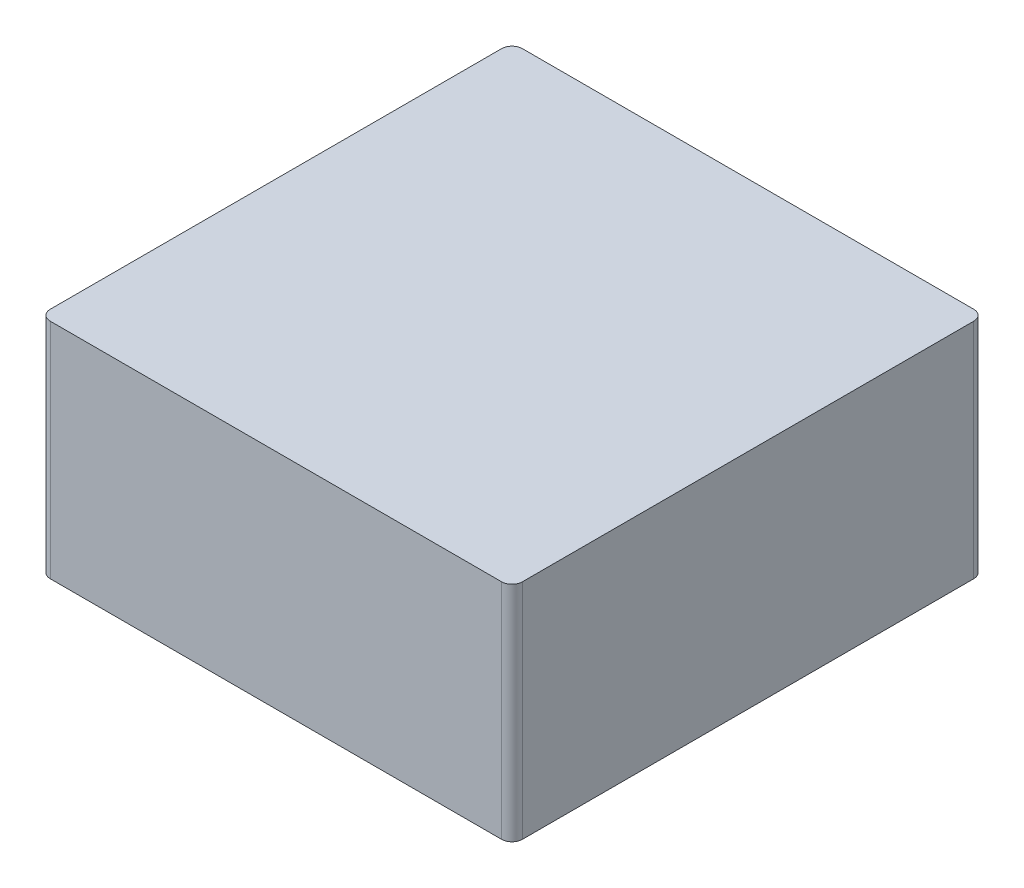
SolidWorks part; units mm, degrees
ref_plane "Front Plane" through (0, 0, 0) normal (0, 0, 1) x (1, 0, 0)
ref_plane "Top Plane" through (0, 0, 0) normal (0, 1, 0) x (1, 0, 0)
ref_plane "Right Plane" through (0, 0, 0) normal (1, 0, 0) x (0, 0, -1)
sketch "Sketch1" plane through (0, 0, 0) normal (0, 1, 0) x (1, 0, 0)
  line L0 (0, 0) -> (0, 85)
  line L1 (0, 85) -> (-85, 85)
  line L2 (-85, 85) -> (-85, 0)
  line L3 (-85, 0) -> (0, 0)
  line L4 (-88, 88) -> (-88, -3)
  line L5 (-88, -3) -> (3, -3)
  line L6 (3, -3) -> (3, 88)
  line L7 (3, 88) -> (-88, 88)
  dimension "D1" = 85
  dimension "D2" = 85
  dimension "D3" = 3
extrude "Boss-Extrude1" add sketch "Sketch1" along normal blind 40
sketch "Sketch2" plane through (0, 40, 0) normal (0, 1, 0) x (1, 0, 0)
  line L0 (-85, 85) -> (-85, 0) construction
  line L1 (-88, 88) -> (3, 88)
  line L2 (-88, 88) -> (-88, -3)
  line L3 (-88, -3) -> (3, -3)
  line L4 (3, 88) -> (3, -3)
  point P6 (-85, 42.5)
extrude "Boss-Extrude2" add sketch "Sketch2" along normal blind 3 contours L2 L3 L4 L1
fillet "Fillet1" radius 2 4 edges at (-88, 21.5, -88) (3, 21.5, -88) (3, 21.5, 3) (-88, 21.5, 3)
sketch "Sketch3" plane through (0, 40, 0) normal (0, -1, 0) x (1, 0, 0)
  line L0 (-85, -85) -> (-85, 0) construction
  line L1 (-85, -42.5) -> (-66.5, -42.5) construction
  line L2 (-66.5, -42.5) -> (-66.5, -29.5) construction
  line L3 (-42.5, 0) -> (-42.5, -23.3666) construction
  line L4 (-85, 0) -> (0, 0) construction
  circle A0 centre (-66.5, -29.5) radius 2.5
  circle A1 centre (-66.5, -55.5) radius 2.5
  circle A2 centre (-18.5, -55.5) radius 2.5
  circle A3 centre (-18.5, -29.5) radius 2.5
  point P0 (-85, -42.5)
  point P1 (-85, -42.5)
  dimension "D3" = 5
  dimension "D1" = 18.5
  dimension "D2" = 13
extrude "Boss-Extrude3" add sketch "Sketch3" along normal blind 3
